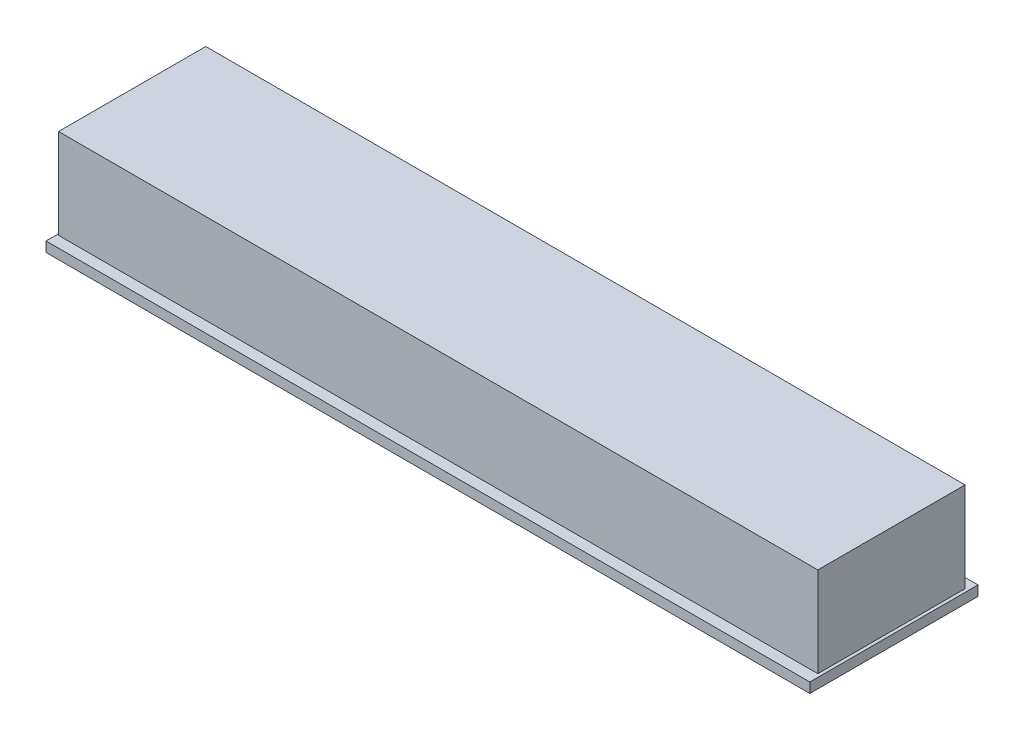
SolidWorks part; units mm, degrees
ref_plane "Front Plane" through (0, 0, 0) normal (0, 0, 1) x (1, 0, 0)
ref_plane "Top Plane" through (0, 0, 0) normal (0, 1, 0) x (1, 0, 0)
ref_plane "Right Plane" through (0, 0, 0) normal (1, 0, 0) x (0, 0, -1)
sketch "Sketch1" plane through (0, 0, 0) normal (0, 1, 0) x (1, 0, 0)
  line L5 (-44.5254, 52.1718) -> (31.9292, 52.1718)
  line L6 (-44.5254, 52.1718) -> (-44.5254, 35.3422)
  line L7 (-44.5254, 35.3422) -> (31.9292, 35.3422)
  line L8 (31.9292, 52.1718) -> (31.9292, 35.3422)
extrude "Boss-Extrude1" add sketch "Sketch1" along normal blind 1 contours L5 L8 L7 L6
sketch "Sketch3" plane through (0, 0, 0) normal (0, 1, 0) x (1, 0, 0)
  line L9 (-44.3866, 36.4571) -> (31.6134, 36.4571)
  line L10 (-44.3866, 36.4571) -> (-44.3866, 51.1939)
  line L11 (-44.3866, 51.1939) -> (31.6134, 51.1939)
  line L12 (31.6134, 36.4571) -> (31.6134, 51.1939)
  dimension "D1" = 76
extrude "Boss-Extrude2" add sketch "Sketch3" along normal blind 10
scale "Scale1" scale about centroid uniform scaling yes scale factor 0.2
